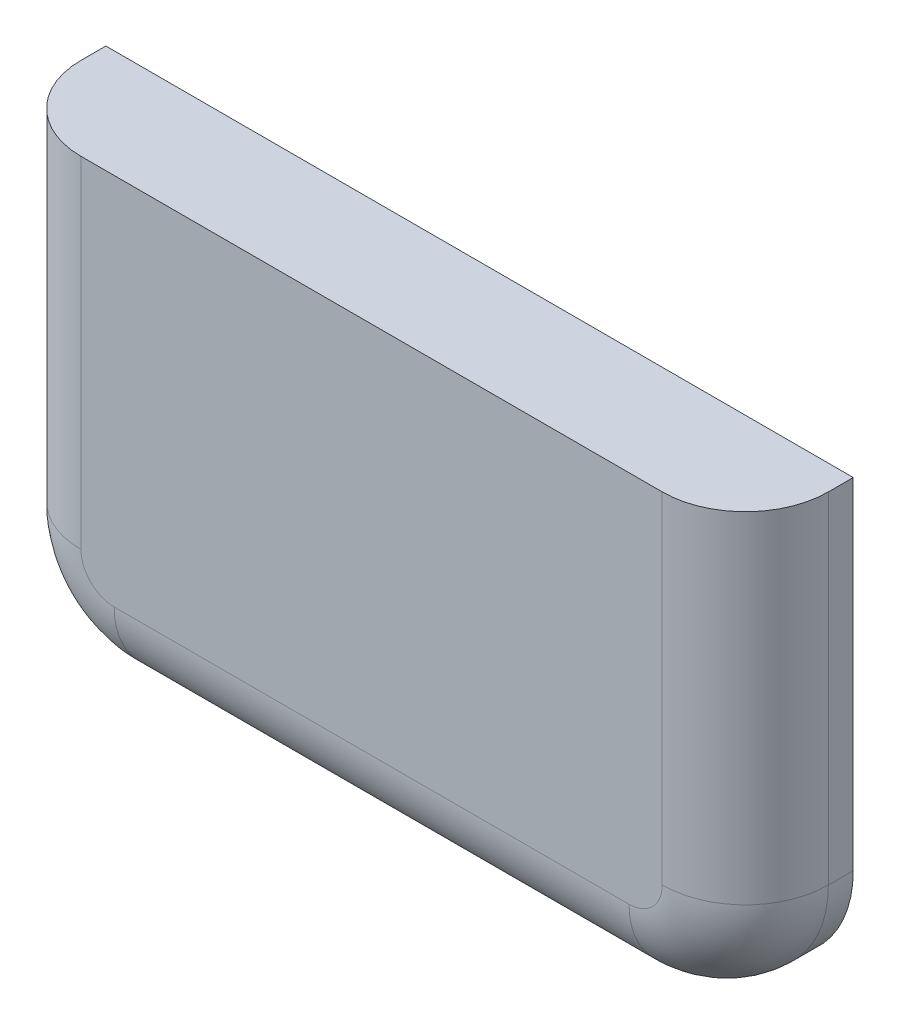
SolidWorks part; units mm, degrees
ref_plane "Alzado" through (0, 0, 0) normal (0, 0, 1) x (1, 0, 0)
ref_plane "Planta" through (0, 0, 0) normal (0, 1, 0) x (1, 0, 0)
ref_plane "Vista lateral" through (0, 0, 0) normal (1, 0, 0) x (0, 0, -1)
sketch "Croquis1" plane through (0, 0, 0) normal (0, 0, 1) x (1, 0, 0)
  line L1 (-225, -137.5) -> (225, -137.5)
  line L2 (-225, -137.5) -> (-225, 137.5)
  line L3 (-225, 137.5) -> (225, 137.5)
  line L4 (225, -137.5) -> (225, 137.5)
  line L5 (-225, -137.5) -> (225, 137.5) construction
  line L6 (-225, 137.5) -> (225, -137.5) construction
  point P0 (0, 0)
  dimension "D1" = 450
  dimension "D2" = 275
extrude "Saliente-Extruir1" add sketch "Croquis1" along normal blind 65 contours L2 L1 L4 L3
fillet "Redondeo1" radius 70 1 edges at (-225, -137.5, 32.5)
fillet "Redondeo2" radius 70 1 edges at (225, -137.5, 32.5)
fillet "Redondeo3" radius 50 5 edges at (-225, 35, 65) (-204.4975, -116.9975, 65) (225, 35, 65) (204.4975, -116.9975, 65) (0, -137.5, 65)
